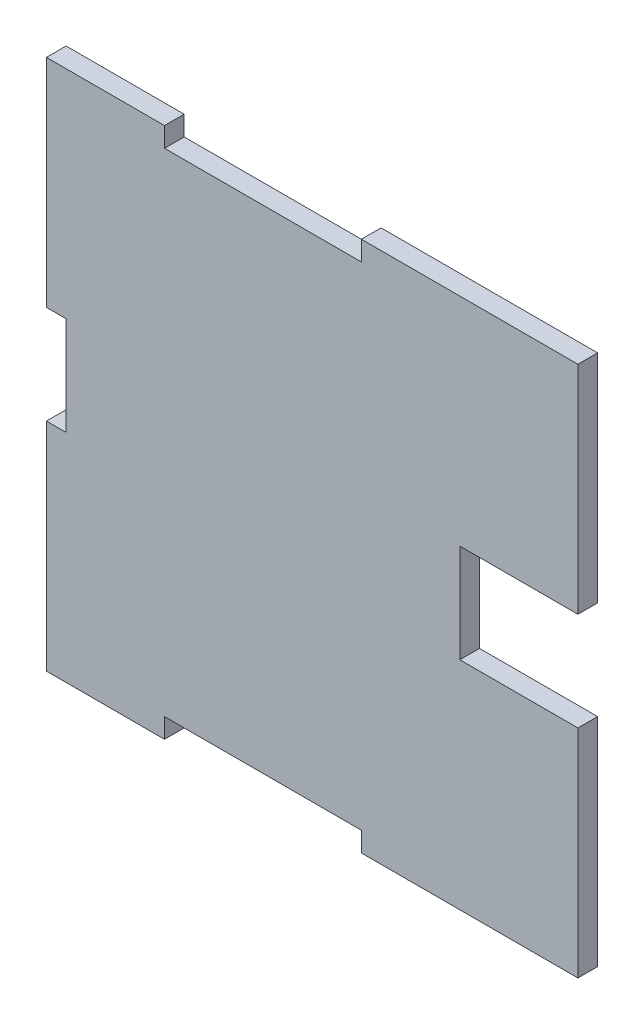
SolidWorks part; units mm, degrees
ref_plane "Front Plane" through (0, 0, 0) normal (0, 0, 1) x (1, 0, 0)
ref_plane "Top Plane" through (0, 0, 0) normal (0, 1, 0) x (1, 0, 0)
ref_plane "Right Plane" through (0, 0, 0) normal (1, 0, 0) x (0, 0, -1)
sketch "Sketch2" plane through (0, 0, 0) normal (0, 0, 1) x (1, 0, 0)
  line L1 (-54, -54) -> (54, -54)
  line L2 (-54, -54) -> (-54, 54)
  line L3 (-54, 54) -> (54, 54)
  line L4 (54, -54) -> (54, 54)
  line L5 (0, 54) -> (0, -54) construction
  line L6 (-54, 0) -> (54, 0) construction
  point P0 (0, 0)
  dimension "D1" = 108
  dimension "D2" = 108
extrude "Boss-Extrude1" add sketch "Sketch2" along normal blind 4
sketch "Sketch3" plane through (0, 0, 0) normal (0, 0, -1) x (-1, 0, 0)
  line L0 (-54, 54) -> (54, 54) construction
  line L1 (-10, 58) -> (10, 58)
  line L2 (-10, 58) -> (-10, 50)
  line L3 (-10, 50) -> (10, 50)
  line L4 (10, 58) -> (10, 50)
  line L5 (0, 50) -> (0, 58) construction
  line L6 (-10, 54) -> (10, 54) construction
  line L7 (54, 54) -> (54, -54) construction
  line L8 (50, -10) -> (58, -10)
  line L9 (50, -10) -> (50, 10)
  line L10 (50, 10) -> (58, 10)
  line L11 (58, -10) -> (58, 10)
  line L12 (54, 10) -> (54, -10) construction
  line L13 (50, 0) -> (58, 0) construction
  line L14 (-54, -54) -> (-54, 54) construction
  line L15 (-58, -10) -> (-50, -10)
  line L16 (-58, -10) -> (-58, 10)
  line L17 (-58, 10) -> (-50, 10)
  line L18 (-50, -10) -> (-50, 10)
  line L19 (-54, 10) -> (-54, -10) construction
  line L20 (-58, 0) -> (-50, 0) construction
  line L21 (54, -54) -> (-54, -54) construction
  line L22 (-10, -58) -> (10, -58)
  line L23 (-10, -58) -> (-10, -50)
  line L24 (-10, -50) -> (10, -50)
  line L25 (10, -58) -> (10, -50)
  line L26 (0, -50) -> (0, -58) construction
  line L27 (-10, -54) -> (10, -54) construction
  point P0 (0, 54)
  point P6 (54, 0)
  point P12 (-54, 0)
  point P18 (0, -54)
  dimension "D1" = 8
  dimension "D2" = 20
  dimension "D3" = 20
  dimension "D4" = 8
  dimension "D5" = 8
  dimension "D6" = 20
  dimension "D7" = 8
  dimension "D8" = 20
extrude "Cut-Extrude1" cut sketch "Sketch3" against normal blind 4
sketch "Sketch4" plane through (0, 0, 0) normal (0, 0, -1) x (-1, 0, 0)
  line L0 (54, -54) -> (10, -54) construction
  line L1 (10, 54) -> (30, 54)
  line L2 (10, 54) -> (10, 50)
  line L3 (10, 50) -> (30, 50)
  line L4 (30, 54) -> (30, 50)
  line L5 (10, -50) -> (30, -50)
  line L6 (10, -50) -> (10, -54)
  line L7 (10, -54) -> (30, -54)
  line L8 (30, -50) -> (30, -54)
  line L10 (-50, 10) -> (-30, 10)
  line L11 (-50, 10) -> (-50, -10)
  line L12 (-50, -10) -> (-30, -10)
  line L13 (-30, 10) -> (-30, -10)
  dimension "D1" = 20
  dimension "D2" = 20
  dimension "D3" = 4
  dimension "D4" = 4
  dimension "D5" = 20
  dimension "D6" = 20
extrude "Cut-Extrude2" cut sketch "Sketch4" against normal blind 4
